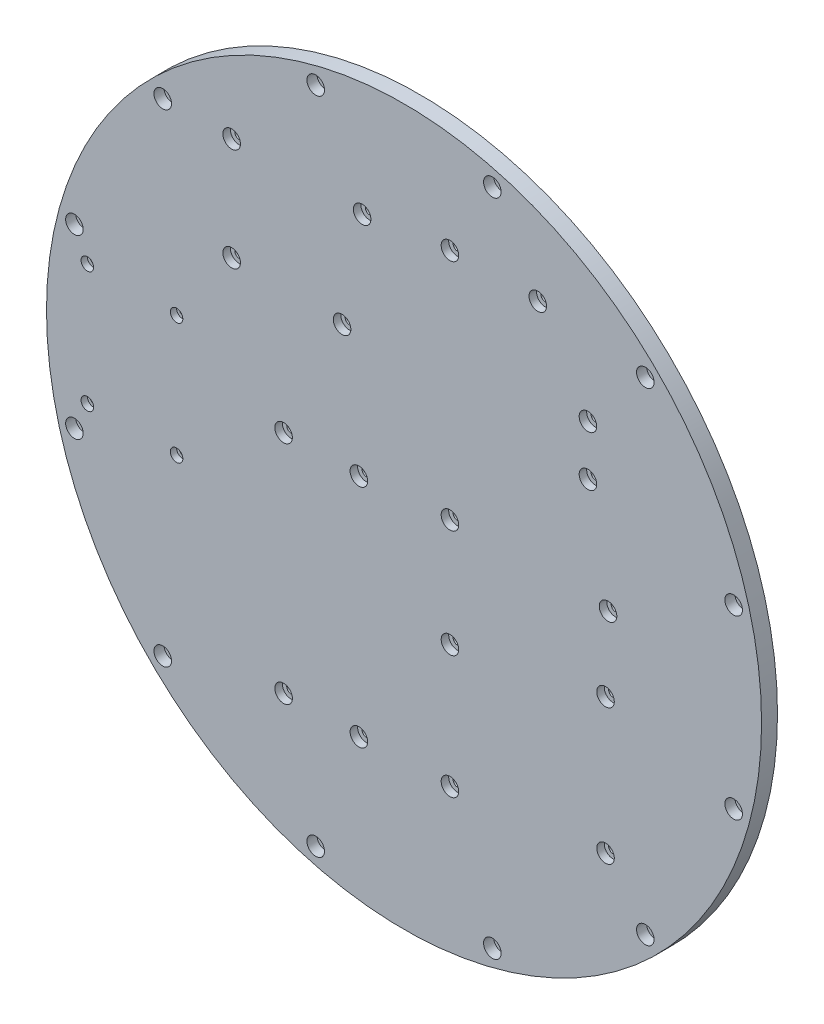
SolidWorks part; units mm, degrees
ref_plane "Plan de face" through (0, 0, 0) normal (0, 0, 1) x (1, 0, 0)
ref_plane "Plan de dessus" through (0, 0, 0) normal (0, 1, 0) x (1, 0, 0)
ref_plane "Plan de droite" through (0, 0, 0) normal (1, 0, 0) x (0, 0, -1)
sketch "Esquisse1" plane through (0, 0, 0) normal (0, 0, 1) x (1, 0, 0)
  line L0 (0, 0) -> (0, 136) construction
  line L1 (0, 0) -> (-35.1994, 131.3659) construction
  circle A3 centre (0, 0) radius 136 construction
  circle A14 centre (-35.1994, 131.3659) radius 1.75
  circle A41 centre (0, 0) radius 142.5
  circle A42 centre (35.1994, 131.3659) radius 1.75
  circle A43 centre (96.1665, 96.1665) radius 1.75
  circle A44 centre (131.3659, 35.1994) radius 1.75
  circle A45 centre (131.3659, -35.1994) radius 1.75
  circle A46 centre (96.1665, -96.1665) radius 1.75
  circle A47 centre (35.1994, -131.3659) radius 1.75
  circle A48 centre (-35.1994, -131.3659) radius 1.75
  circle A49 centre (-96.1665, -96.1665) radius 1.75
  circle A50 centre (-131.3659, -35.1994) radius 1.75
  circle A51 centre (-131.3659, 35.1994) radius 1.75
  circle A52 centre (-96.1665, 96.1665) radius 1.75
  point P31 (0, 0)
  point P34 (0, 0)
  point P41 (0, 0)
  dimension "D1" = 272
  dimension "D3" = 3.5
  dimension "D4" = 285
  dimension "D2" = 15
extrude "Boss.-Extru.1" add sketch "Esquisse1" along normal blind 6.35
sketch "Esquisse2" plane through (0, 0, 6.35) normal (0, 0, 1) x (1, 0, 0)
  circle A12 centre (35.1994, 131.3659) radius 3.5
  circle A13 centre (96.1665, 96.1665) radius 3.5
  circle A14 centre (131.3659, 35.1994) radius 3.5
  circle A15 centre (131.3659, -35.1994) radius 3.5
  circle A16 centre (96.1665, -96.1665) radius 3.5
  circle A17 centre (35.1994, -131.3659) radius 3.5
  circle A18 centre (-35.1994, -131.3659) radius 3.5
  circle A19 centre (-96.1665, -96.1665) radius 3.5
  circle A20 centre (-131.3659, -35.1994) radius 3.5
  circle A21 centre (-131.3659, 35.1994) radius 3.5
  circle A22 centre (-96.1665, 96.1665) radius 3.5
  circle A23 centre (-35.1994, 131.3659) radius 3.5
  point P20 (0, 0)
  point P27 (0, 0)
  dimension "D1" = 7
extrude "Enlèv. mat.-Extru.1" cut sketch "Esquisse2" against normal blind 4
sketch "Esquisse3" plane through (0, 0, 6.35) normal (0, 0, 1) x (1, 0, 0)
  line L0 (-126.2141, -24.13) -> (-126.2141, 24.13) construction
  line L1 (-126.2141, 24.13) -> (-90.6541, 24.13) construction
  line L2 (-90.6541, 24.13) -> (-90.6541, -24.13) construction
  line L3 (-90.6541, -24.13) -> (-126.2141, -24.13) construction
  circle A0 centre (0, 0) radius 128.5 construction
  circle A3 centre (-126.2141, -24.13) radius 1.25
  circle A4 centre (-126.2141, 24.13) radius 1.25
  circle A5 centre (-90.6541, 24.13) radius 1.25
  circle A6 centre (-90.6541, -24.13) radius 1.25
  dimension "D1" = 257
  dimension "D2" = 35.56
  dimension "D4" = 2.5
  dimension "D3" = 48.26
extrude "Enlèv. mat.-Extru.2" cut sketch "Esquisse3" against normal up to next
sketch "Esquisse4" plane through (0, 0, 6.35) normal (0, 0, 1) x (1, 0, 0)
  circle A0 centre (-126.2141, -24.13) radius 2.5
  circle A1 centre (-126.2141, 24.13) radius 2.5
  circle A2 centre (-90.6541, 24.13) radius 2.5
  circle A3 centre (-90.6541, -24.13) radius 2.5
  dimension "D1" = 5
extrude "Enlèv. mat.-Extru.3" cut sketch "Esquisse4" against normal blind 2.5
sketch "Esquisse5" plane through (0, 0, 6.35) normal (0, 0, 1) x (1, 0, 0)
  circle A0 centre (-48, -85) radius 1.75
  circle A1 centre (-48, 5) radius 1.75
  circle A2 centre (-18, 5) radius 1.75
  circle A3 centre (-18, -85) radius 1.75
  circle A4 centre (0, 0) radius 142.5 construction
  circle A5 centre (0, 0) radius 142.5 construction
  dimension "D4" = 3.5
  dimension "D1" = 90
  dimension "D2" = 30
  dimension "D3" = 5
  dimension "D5" = 18
extrude "Enlèv. mat.-Extru.4" cut sketch "Esquisse5" against normal up to next
sketch "Esquisse6" plane through (0, 0, 6.35) normal (0, 0, 1) x (1, 0, 0)
  circle A0 centre (-48, -85) radius 3.5
  circle A1 centre (-18, -85) radius 3.5
  circle A2 centre (-48, 5) radius 3.5
  circle A3 centre (-18, 5) radius 3.5
  dimension "D1" = 7
extrude "Enlèv. mat.-Extru.5" cut sketch "Esquisse6" against normal blind 3
sketch "Esquisse7" plane through (0, 0, 6.35) normal (0, 0, 1) x (1, 0, 0)
  circle A0 centre (-68.7, 55) radius 1.75
  circle A1 centre (-68.7, 96) radius 1.75
  circle A2 centre (-24.7, 54) radius 1.75
  circle A3 centre (-16.7, 96) radius 1.75
  circle A5 centre (-18, 5) radius 3.5 construction
  circle A7 centre (-48, 5) radius 3.5 construction
  circle A8 centre (-18, 5) radius 3.5 construction
  circle A9 centre (-48, 5) radius 3.5 construction
  dimension "D5" = 3.5
  dimension "D7" = 50
  dimension "D1" = 44
  dimension "D2" = 41
  dimension "D3" = 42
  dimension "D4" = 52
  dimension "D6" = 6.7
extrude "Enlèv. mat.-Extru.6" cut sketch "Esquisse7" against normal up to next
sketch "Esquisse8" plane through (0, 0, 6.35) normal (0, 0, 1) x (1, 0, 0)
  circle A0 centre (-68.7, 55) radius 3.5
  circle A1 centre (-68.7, 96) radius 3.5
  circle A2 centre (-24.7, 54) radius 3.5
  circle A3 centre (-16.7, 96) radius 3.5
  dimension "D1" = 7
extrude "Enlèv. mat.-Extru.7" cut sketch "Esquisse8" against normal blind 3
sketch "Esquisse9" plane through (0, 0, 6.35) normal (0, 0, -1) x (-1, 0, 0)
  circle A0 centre (-18.3, 101) radius 1.75
  circle A1 centre (-18.3, 8) radius 1.75
  circle A2 centre (-53.3, 101) radius 1.75
  circle A3 centre (-81.3, 8) radius 1.75
  circle A4 centre (-73.3, 69.5) radius 1.75
  circle A6 centre (16.7, 96) radius 1.75 construction
  circle A7 centre (16.7, 96) radius 1.75 construction
  circle A8 centre (-73.3, 49.5) radius 1.75
  point P15 (-59.3919, 57.414)
  dimension "D1" = 3.5
  dimension "D2" = 93
  dimension "D3" = 35
  dimension "D4" = 55
  dimension "D5" = 63
  dimension "D6" = 35
  dimension "D7" = 31.5
  dimension "D8" = 5
  dimension "D9" = 51.5
extrude "Enlèv. mat.-Extru.8" cut sketch "Esquisse9" along normal up to next
sketch "Esquisse10" plane through (0, 0, 6.35) normal (0, 0, 1) x (1, 0, 0)
  circle A0 centre (18.3, 8) radius 3.5
  circle A1 centre (18.3, 101) radius 3.5
  circle A2 centre (53.3, 101) radius 3.5
  circle A3 centre (81.3, 8) radius 3.5
  circle A4 centre (73.3, 69.5) radius 3.5
  circle A5 centre (73.3, 49.5) radius 3.5
  dimension "D1" = 7
extrude "Enlèv. mat.-Extru.9" cut sketch "Esquisse10" against normal blind 3
sketch "Esquisse11" plane through (0, 0, 6.35) normal (0, 0, -1) x (-1, 0, 0)
  circle A0 centre (-18.3, -35) radius 1.75
  circle A1 centre (-18.3, -84) radius 1.75
  circle A2 centre (-80.3, -22) radius 1.75
  circle A3 centre (-80.3, -76) radius 1.75
  circle A7 centre (-18.3, 8) radius 1.75 construction
  circle A8 centre (-18.3, 8) radius 1.75 construction
  dimension "D1" = 3.5
  dimension "D2" = 49
  dimension "D6" = 30
  dimension "D3" = 62
  dimension "D4" = 13
  dimension "D5" = 54
extrude "Enlèv. mat.-Extru.10" cut sketch "Esquisse11" along normal up to next
sketch "Esquisse12" plane through (0, 0, 6.35) normal (0, 0, 1) x (1, 0, 0)
  circle A0 centre (18.3, -84) radius 3.5
  circle A1 centre (18.3, -35) radius 3.5
  circle A2 centre (80.3, -22) radius 3.5
  circle A3 centre (80.3, -76) radius 3.5
  dimension "D1" = 7
extrude "Enlèv. mat.-Extru.11" cut sketch "Esquisse12" against normal blind 3
